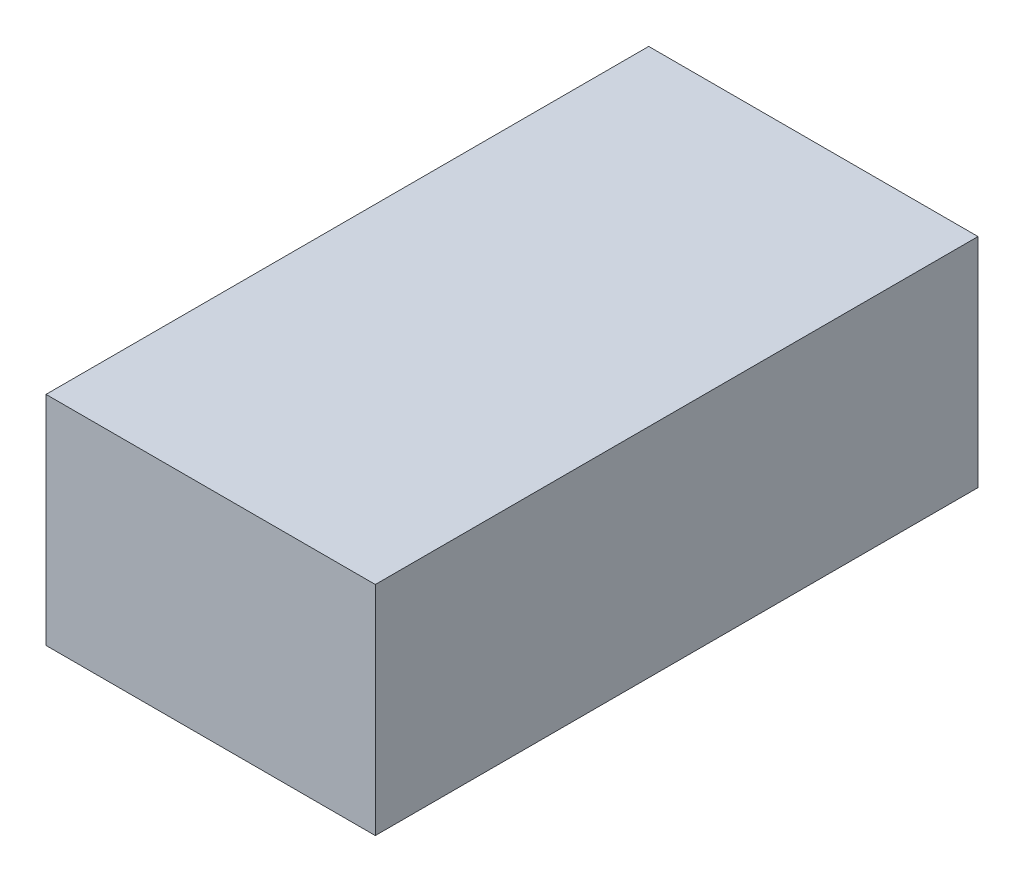
SolidWorks part; units mm, degrees
ref_plane "Front Plane" through (0, 0, 0) normal (0, 0, 1) x (1, 0, 0)
ref_plane "Top Plane" through (0, 0, 0) normal (0, 1, 0) x (1, 0, 0)
ref_plane "Right Plane" through (0, 0, 0) normal (1, 0, 0) x (0, 0, -1)
sketch "Sketch1" plane through (0, 0, 0) normal (0, 0, 1) x (1, 0, 0)
  line L1 (0, 0) -> (26.5, 0)
  line L2 (0, 0) -> (0, -17.5)
  line L3 (0, -17.5) -> (26.5, -17.5)
  line L4 (26.5, 0) -> (26.5, -17.5)
  dimension "D1" = 26.5
  dimension "D2" = 17.5
extrude "Boss-Extrude1" add sketch "Sketch1" along normal blind 48.5
